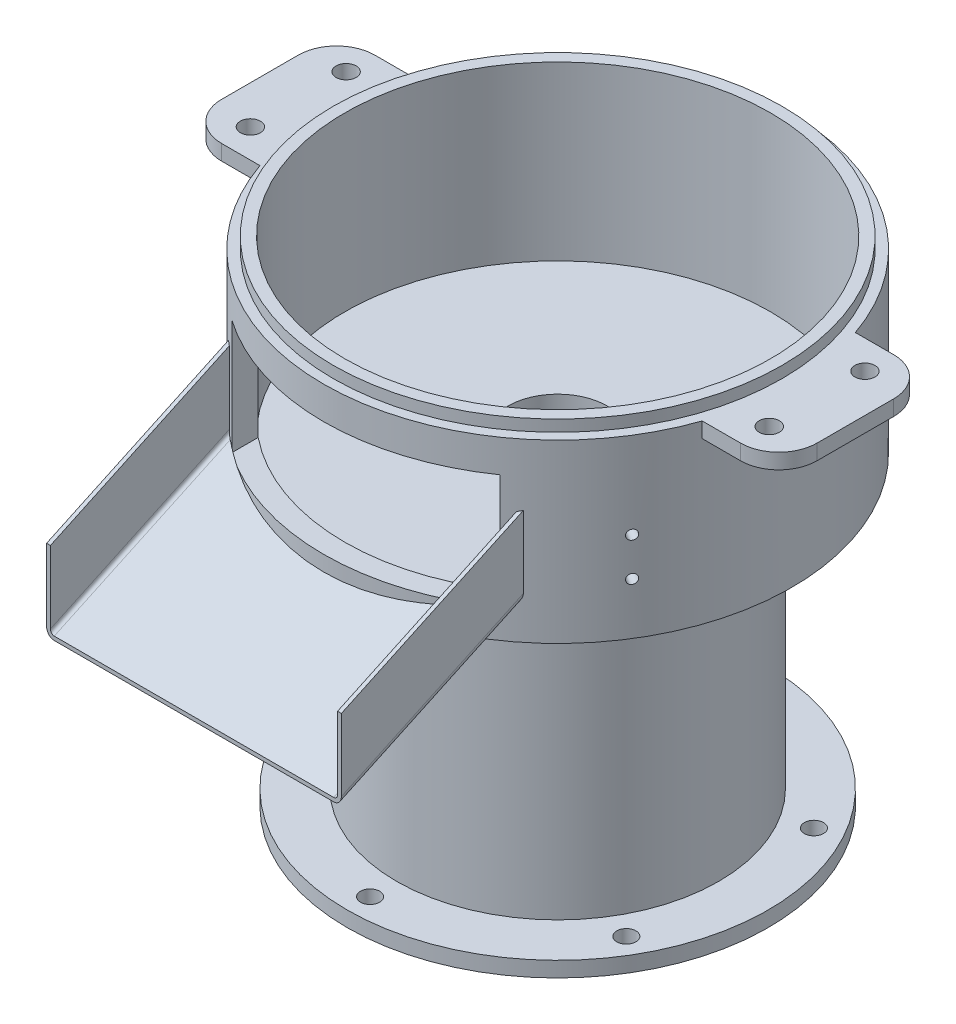
SolidWorks part; units mm, degrees
ref_plane "Front Plane" through (0, 0, 0) normal (0, 0, 1) x (1, 0, 0)
ref_plane "Top Plane" through (0, 0, 0) normal (0, 1, 0) x (1, 0, 0)
ref_plane "Right Plane" through (0, 0, 0) normal (1, 0, 0) x (0, 0, -1)
sketch "Sketch1" plane through (0, 0, 0) normal (0, 0, 1) x (1, 0, 0)
  line L0 (0, 0) -> (0, -293.7739) construction
  line L1 (122.25, -6) -> (122.25, -98)
  line L2 (122.25, -98) -> (84.15, -98)
  line L3 (30, -98) -> (30, -250)
  line L4 (30, -250) -> (78.15, -250)
  line L5 (110, -250) -> (110, -258)
  line L6 (110, -258) -> (19, -258)
  line L7 (19, -258) -> (19, -244.25)
  line L8 (19, -244.25) -> (21, -244.25)
  line L9 (21, -244.25) -> (21, -106.25)
  line L10 (21, -106.25) -> (26, -106.25)
  line L11 (26, -106.25) -> (26, -90)
  line L12 (26, -90) -> (111.25, -90)
  line L13 (111.25, -90) -> (111.25, 0)
  line L14 (111.25, 0) -> (117.25, 0)
  line L15 (117.25, 0) -> (117.25, -6)
  line L16 (117.25, -6) -> (122.25, -6)
  line L17 (78.15, -98) -> (78.15, -250)
  line L18 (84.15, -98) -> (84.15, -250)
  line L19 (78.15, -98) -> (30, -98)
  line L20 (84.15, -250) -> (110, -250)
  point P20 (23.5, -106.25)
  point P25 (110, -254)
  dimension "D2" = 8
  dimension "D4" = 52
  dimension "D5" = 42
  dimension "D6" = 8
  dimension "D7" = 90
  dimension "D8" = 16.25
  dimension "D9" = 250
  dimension "D3" = 244.5
  dimension "D14" = 5
  dimension "D15" = 6
  dimension "D13" = 11
  dimension "D11" = 60
  dimension "D12" = 38
  dimension "D16" = 6
  dimension "D17" = 168.3
  dimension "D18" = 220
  dimension "D19" = 138
revolve "Revolve1" add sketch "Sketch1" angle 360 about L0
sketch "Sketch2" plane through (0, 0, 0) normal (0, 0, 1) x (1, 0, 0)
  line L0 (70, -83) -> (-70, -83)
  line L1 (-70, -83) -> (-70, -23)
  line L2 (70, -23) -> (70, -83)
  line L3 (70, -23) -> (-70, -23)
  line L4 (-122.25, -98) -> (122.25, -98) construction
  point P4 (0, -83)
  dimension "D1" = 140
  dimension "D2" = 60
  dimension "D3" = 15
extrude "Cut-Extrude1" cut sketch "Sketch2" along normal through all from surface
sketch "Sketch3" plane through (0, -258, 0) normal (0, -1, 0) x (1, 0, 0)
  circle A0 centre (0, 0) radius 98 construction
  circle A2 centre (0, 98) radius 5
  dimension "D2" = 10
  dimension "D1" = 196
extrude "Cut-Extrude2" cut sketch "Sketch3" against normal up to surface (8 mm away) up to face at (0, -250, 110)
pattern_circular "CirPattern1" count 6 over 360 about axis through (0, 0, 0) along (0, 1, 0) of "Cut-Extrude2"
sketch "Sketch4" plane through (0, -6, 0) normal (0, 1, 0) x (1, 0, 0)
  line L0 (0, 0) -> (155.5208, 0) construction
  line L1 (115.5208, 40) -> (155.5208, 40)
  line L2 (115.5208, 40) -> (115.5208, -40)
  line L3 (115.5208, -40) -> (155.5208, -40)
  line L4 (155.5208, 40) -> (155.5208, -40)
  line L5 (0, 0) -> (0, 179.3817) construction
  line L6 (-155.5208, 40) -> (-155.5208, -40)
  line L7 (-115.5208, -40) -> (-155.5208, -40)
  line L8 (-115.5208, 40) -> (-115.5208, -40)
  line L9 (-115.5208, 40) -> (-155.5208, 40)
  circle A0 centre (0, 0) radius 122.25
  circle A1 centre (135.5208, 25) radius 5.25
  circle A2 centre (135.5208, -25) radius 5.25
  circle A3 centre (-135.5208, 25) radius 5.25
  circle A4 centre (-135.5208, -25) radius 5.25
  point P8 (115.5208, 0)
  circle M14 centre (0, 0) radius 122.25
  dimension "D1" = 244.5
  dimension "D4" = 10.5
  dimension "D2" = 80
  dimension "D3" = 40
  dimension "D5" = 15
  dimension "D6" = 20
extrude "Boss-Extrude1" add sketch "Sketch4" against normal blind 8 contours L9 L6 L7 A3 A4 M14 | L4 L1 L3 A2 A1 M14
fillet "Fillet1" radius 20 4 edges at (155.5208, -10, 40) (155.5208, -10, -40) (-155.5208, -10, -40) (-155.5208, -10, 40)
ref_plane "Plane1" through (0, 0, 190) normal (0, 0, 1) x (1, 0, 0)
sketch "Sketch6" plane through (0, 0, 0) normal (1, 0, 0) x (0, 0, -1)
  line L0 (-122.25, -83) -> (-190, -114.5923) construction
  line L1 (-122.25, -98) -> (122.25, -98) construction
  line L2 (-190, 141.9) -> (-190, -141.9) construction
  dimension "D1" = 25
sketch "Sketch5" plane through (0, 0, 190) normal (0, 0, 1) x (1, 0, 0)
  line L1 (-75, -72.5923) -> (75, -72.5923)
  line L2 (-75, -72.5923) -> (-75, -122.5923)
  line L3 (-75, -122.5923) -> (75, -122.5923)
  line L4 (75, -72.5923) -> (75, -122.5923)
  line L5 (70, -83) -> (70, -23) construction
  line L7 (-77, -124.5923) -> (77, -124.5923)
  line L8 (77, -70.5923) -> (77, -124.5923)
  line L9 (-77, -70.5923) -> (77, -70.5923)
  line L10 (-77, -70.5923) -> (-77, -124.5923)
  line L11 (-75, -82.5923) -> (-77, -82.5923)
  line L12 (75, -82.5923) -> (77, -82.5923)
  point P8 (75, -97.5923)
  dimension "D1" = 150
  dimension "D2" = 50
  dimension "D3" = 8
  dimension "D4" = 5
  dimension "D5" = 2
  dimension "D6" = 40
extrude "Boss-Extrude2" add sketch "Sketch5" along direction (0, -0.4226, 0.9063) on the side against the normal up to surface (104.8728 mm away) separate body contours L12 L4 L3 L2 L11 L10 L7 L8
ref_plane "Plane2" through (103.6739, 0, 64.7826) normal (0.848, 0, 0.5299) x (0, 1, 0)
sketch "Sketch8" plane through (103.6739, 0, 64.7826) normal (0.848, 0, 0.5299) x (0, 1, 0)
  line L2 (-98, 122.25) -> (-98, -122.25) construction
  circle A0 centre (-51, 0) radius 2.5
  circle A1 centre (-71, 0) radius 2.5
  dimension "D1" = 5
  dimension "D2" = 20
  dimension "D3" = 27
extrude "Cut-Extrude3" cut sketch "Sketch8" against normal up to next
fillet "Fillet2" radius 2 2 edges at (75, -100.8019, 143.2702) (-75, -100.8019, 143.2702)
fillet "Fillet3" radius 4 2 edges at (77, -102.4318, 142.4765) (-77, -102.4318, 142.4765)
equation "\"d_ext_rouleau\"= 90"
equation "\"epaisseur_rouleau\"=80"
equation "\"alesage-rouleau\"= 52"
equation "\"jeu_dent_rouleau\"= 2"
equation "\"profondeur_dent_rouleau\"=4"
equation "\"n_dent_roueau\"= 15"
equation "\"d_ext_roulement_rouleau\"= 42"
equation "\"d_int_roulement_rouleau\"= 20"
equation "\"B_roulement_rouleau\"= 12"
equation "\"r_roulement_rouleau\"= 0.6"
equation "\"d_bille_roulement_rouleau\"= 8"
equation "\"F_anneau_alesage_rouleau\"=1.85"
equation "\"G_anneau_alesage_rouleau\"=47.5"
equation "\"K_anneau_alesage_rouleau\"=3.75"
equation "\"d_vis_flasque_rouleau\"=5"
equation "\"l-x_vis_flasque_rouleau\"=4"
equation "\"g_anneau_arbre_rouleau\"=19"
equation "\"f_anneau_arbre_rouleau\"=1.3"
equation "\"k_anneau_arbre_rouleau\"=1.5"
equation "\"entrax_vis_rouleau\"=65"
equation "\"d_granulat\"= 8"
equation "\"h_matrice\"= 22"
equation "\"d_matrice\"= 220"
equation "\"zone_vide_matrice\" = 48"
equation "\"d_alesage_matrice\"=20"
equation "\"a_clavette_alesage_matrice\"=6"
equation "\"B_roulement_matrice\"= 12"
equation "\"d_ext_roulement_matrice\"= 42"
equation "\"d_int_roulement_matrice\"= 20"
equation "\"r_roulement_matrice\"= 1"
equation "\"h_epaulement_arbre_matrice\" = 80"
equation "\"j_clavette_arbre_matrice\" = 6"
equation "\"g_anneaux_arbre_matrice\" = 19"
equation "\"f_anneaux_arbre_matrice\" = 1.3"
equation "\"B_roulement_bc_arbre_matrice\"= 10"
equation "\"e_anneaux_arbre_matrice\" = 1.2"
equation "\"h_polie_matrice\" = 40"
equation "\"l_arbre_matrice\" = 300"
equation "\"d_int_ecrou_encouch_matrice\" = 20"
equation "\"d_ext_ecrou_encouch_matrice\" = 32"
equation "\"b_ecrou_encouch_matrice\" = 6"
equation "\"s_ecrou_encouch_matrice\" = 4"
equation "\"G_ecrou_encouch_matrice\" = 1"
equation "\"E_ecrou_encouch_matrice\" = 4"
equation "\"d_ext_roulement_conique_matrice\"=52"
equation "\"D4@Sketch1\"=\"d_ext_roulement_conique_matrice\""
equation "\"d_ext_roulement_bc_matrice\"=42"
equation "\"D5@Sketch1\"=\"d_ext_roulement_bc_matrice\""
equation "\"D7@Sketch1\"=\"h_epaulement_arbre_matrice\"+10"
equation "\"b_roulement_conique_matrice\"=16.25"
equation "\"D8@Sketch1\"=\"b_roulement_conique_matrice\""
equation "\"d_tube_sup_carter\"=244.5"
equation "\"D3@Sketch1\"=\"d_tube_sup_carter\""
equation "\"d_tube_inf_catrer\"= 168.3"
equation "\"e_tube_inf_carter\"= 6"
equation "\"e_tube_sup_carter\"=12"
equation "\"D13@Sketch1\"=\"e_tube_sup_carter\"-1"
equation "\"D16@Sketch1\"=\"e_tube_inf_carter\""
equation "\"D17@Sketch1\"=\"d_tube_inf_catrer\""
equation "\"e_tole\" = 8"
equation "\"D2@Sketch1\"=\"e_tole\""
equation "\"D6@Sketch1\"=\"e_tole\""
equation "\"entraxe_vis_carter\" = 196"
equation "\"D1@Sketch3\"=\"entraxe_vis_carter\""
equation "\"D1@Sketch4\"=\"d_tube_sup_carter\""
